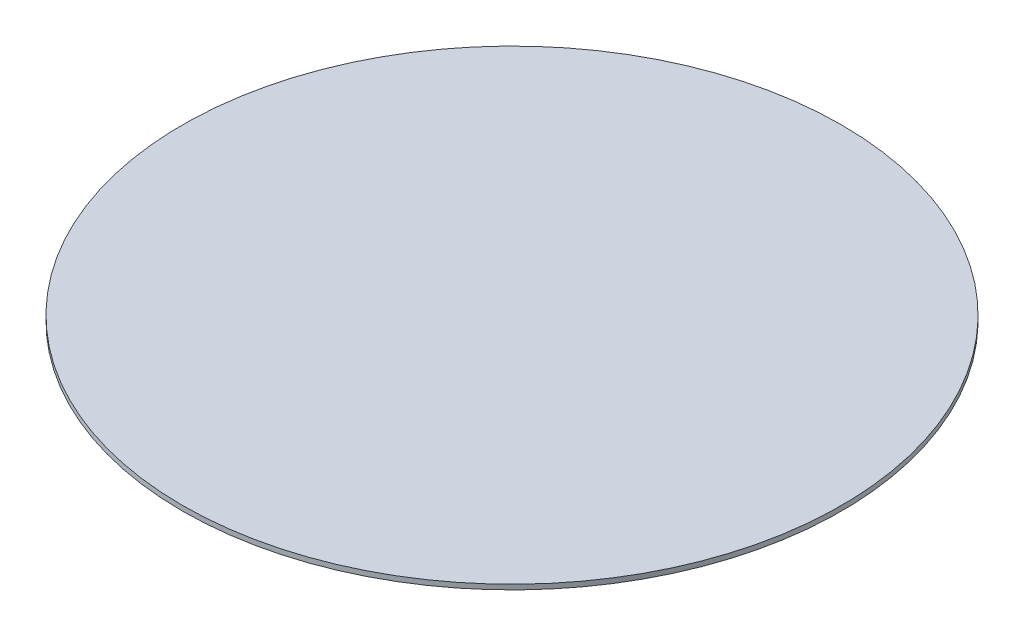
SolidWorks part; units mm, degrees
ref_plane "Спереди" through (0, 0, 0) normal (0, 0, 1) x (1, 0, 0)
ref_plane "Сверху" through (0, 0, 0) normal (0, 1, 0) x (1, 0, 0)
ref_plane "Справа" through (0, 0, 0) normal (1, 0, 0) x (0, 0, -1)
sketch "Эскиз1" plane through (0, 0, 0) normal (0, 1, 0) x (1, 0, 0)
  circle A0 centre (0, 0) radius 200
  dimension "D1" = 400
extrude "Бобышка-Вытянуть1" add sketch "Эскиз1" along normal blind 3
